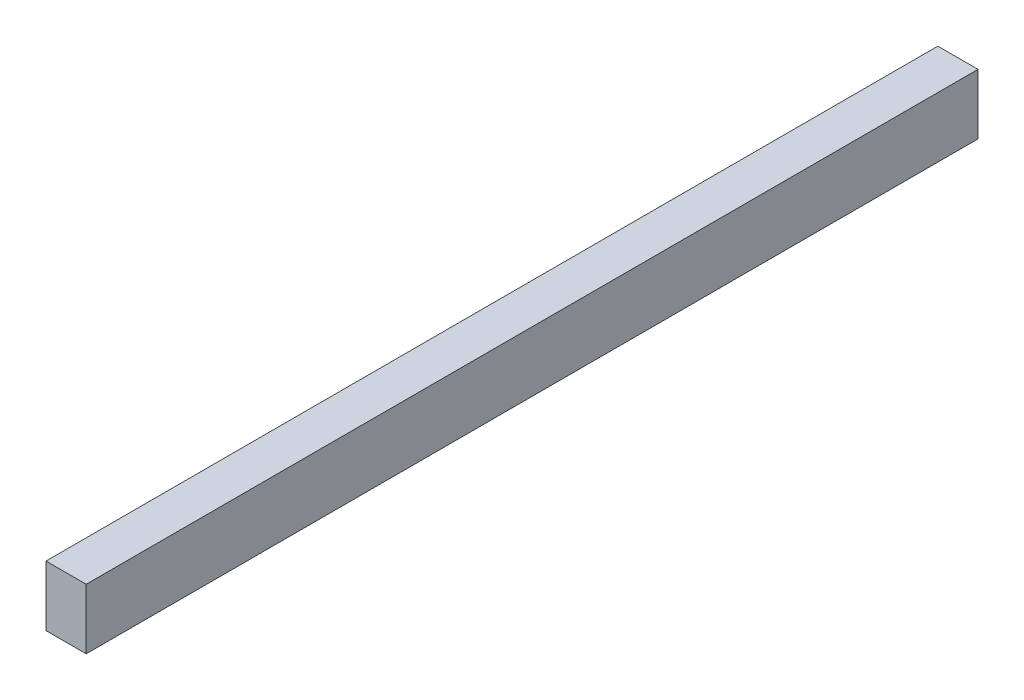
SolidWorks part; units mm, degrees
ref_plane "Płaszczyzna przednia" through (0, 0, 0) normal (0, 0, 1) x (1, 0, 0)
ref_plane "Płaszczyzna górna" through (0, 0, 0) normal (0, 1, 0) x (1, 0, 0)
ref_plane "Płaszczyzna prawa" through (0, 0, 0) normal (1, 0, 0) x (0, 0, -1)
sketch "Szkic1" plane through (0, 0, 0) normal (0, 0, 1) x (1, 0, 0)
  line L1 (0, 0) -> (100, 0)
  line L2 (0, 0) -> (0, 150)
  line L3 (0, 150) -> (100, 150)
  line L4 (100, 0) -> (100, 150)
  dimension "D1" = 100
  dimension "D2" = 150
extrude "Dodanie-wyciągnięcie1" add sketch "Szkic1" along normal blind 2220
sketch "Szkic2" plane through (0, 0, 0) normal (1, 0, 0) x (0, 0, -1)
  line L0 (-100, 150) -> (-100, 0)
  line L1 (-2220, 150) -> (0, 150) construction
  line L2 (-2220, 0) -> (0, 0) construction
  line L3 (-2120, 150) -> (-2120, 0)
  line L4 (-2220, 0) -> (-2220, 150) construction
  line L5 (0, 0) -> (0, 150) construction
  dimension "D1" = 100
  dimension "D2" = 100
split line "Linia podziałowa1"
